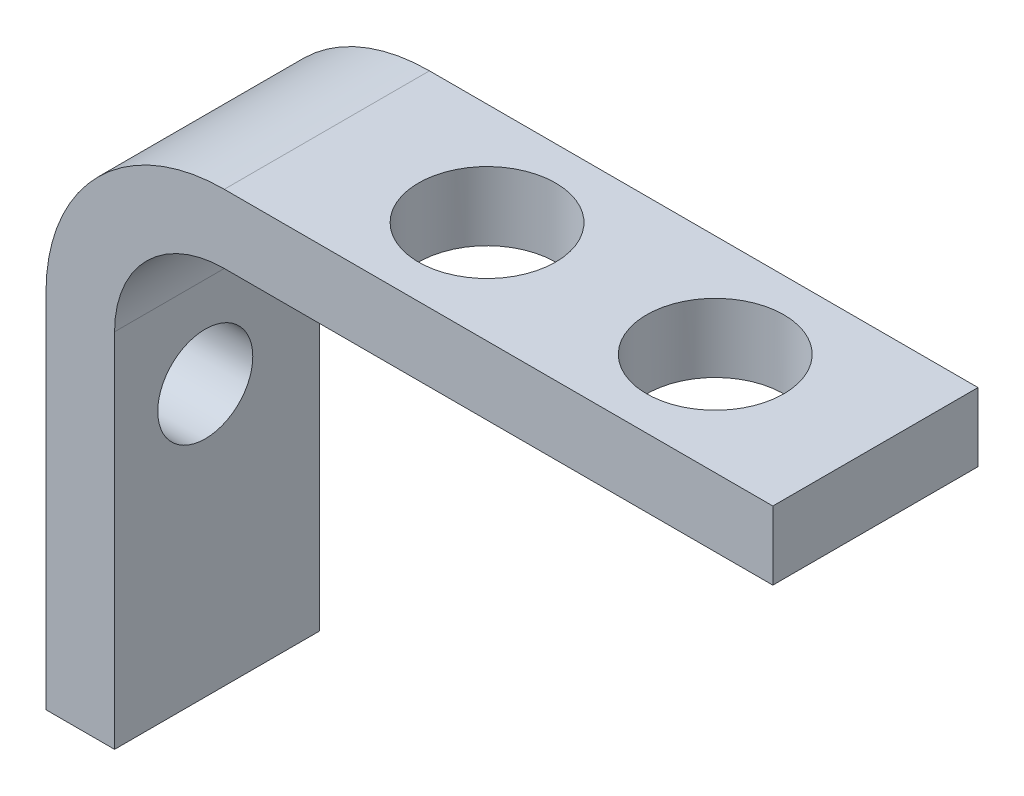
SolidWorks part; units mm, degrees
material "6061 Alloy"
ref_plane "Front Plane" through (0, 0, 0) normal (0, 0, 1) x (1, 0, 0)
ref_plane "Top Plane" through (0, 0, 0) normal (0, 1, 0) x (1, 0, 0)
ref_plane "Right Plane" through (0, 0, 0) normal (1, 0, 0) x (0, 0, -1)
sketch "Sketch1" plane through (0, 0, 0) normal (0, 0, 1) x (1, 0, 0)
  line L0 (0, 0) -> (0, 8.3725)
  line L1 (2.54, 10.9125) -> (15.24, 10.9125)
  line L2 (-1.5875, 0) -> (-1.5875, 8.3725)
  line L3 (2.54, 12.5) -> (15.24, 12.5)
  line L4 (-1.5875, 0) -> (0, 0)
  line L5 (15.24, 10.9125) -> (15.24, 12.5)
  arc A0 (0, 8.3725) -> (2.54, 10.9125) centre (2.54, 8.3725) cw
  arc A1 (-1.5875, 8.3725) -> (2.54, 12.5) centre (2.54, 8.3725) cw
  dimension "D1" = 2.54
  dimension "D2" = 12.7
  dimension "D3" = 12.5
  dimension "D4" = 1.5875
extrude "Boss-Extrude1" add sketch "Sketch1" along normal blind 4.75
sketch "Sketch2" plane through (0, 0, 0) normal (1, 0, 0) x (0, 0, -1)
  line L4 (0, 0) -> (0, 8.3725)
  line L5 (0, 8.3725) -> (-4.75, 8.3725)
  line L6 (-4.75, 8.3725) -> (-4.75, 0)
  line L7 (-4.75, 0) -> (0, 0)
  line L8 (0, 0) -> (0, 8.3725)
  line L9 (0, 8.3725) -> (-4.75, 8.3725)
  line L10 (-4.75, 8.3725) -> (-4.75, 0)
  line L11 (-4.75, 0) -> (0, 0)
  circle A2 centre (-2.65, 6.277) radius 2.0955
  circle A3 centre (-2.65, 6.277) radius 1.1
  dimension "D1" = 0
extrude "Cut-Extrude1" cut sketch "Sketch2" against normal up to next (1.5875 mm away) from surface at 0 contours A3 starting at face at (0, 4.1863, 2.375)
sketch "Sketch3" plane through (0, 10.9125, 0) normal (0, -1, 0) x (1, 0, 0)
  line L0 (15.24, 2.375) -> (2.54, 2.375) construction
  line L1 (15.24, 4.75) -> (15.24, 0) construction
  line L2 (2.54, 4.75) -> (2.54, 0) construction
  circle A0 centre (6.2484, 2.375) radius 1.5875
  circle A1 centre (11.5316, 2.375) radius 1.5875
  dimension "D1" = 3.7084
  dimension "D3" = 5.2832
  dimension "D2" = 3.7084
extrude "Cut-Extrude2" cut sketch "Sketch3" against normal blind 2.54 contours L0 A0 | L0 A0 | L0 A1 | L0 A1
